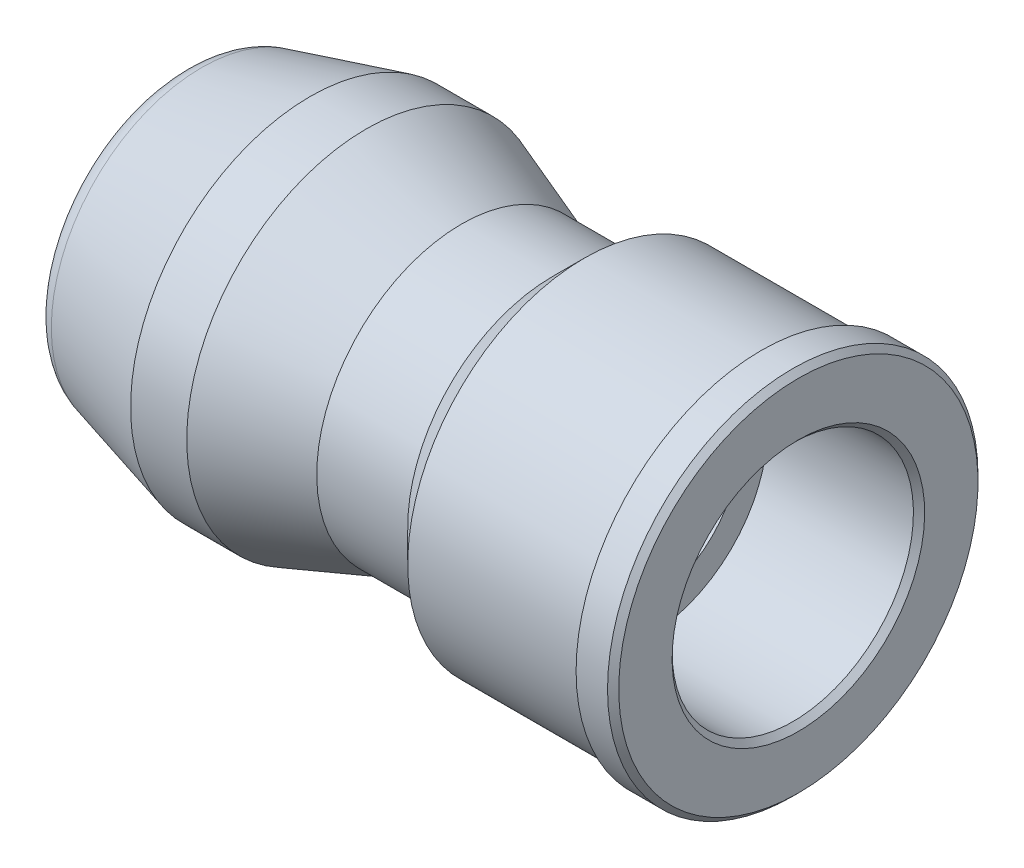
SolidWorks part; units mm, degrees
ref_plane "Front Plane" through (0, 0, 0) normal (0, 0, 1) x (1, 0, 0)
ref_plane "Top Plane" through (0, 0, 0) normal (0, 1, 0) x (1, 0, 0)
ref_plane "Right Plane" through (0, 0, 0) normal (1, 0, 0) x (0, 0, -1)
sketch "Sketch1" plane through (0, 0, 0) normal (0, 0, 1) x (1, 0, 0)
  line L0 (0, 0) -> (0, 2.58)
  line L1 (0, 2.58) -> (2.3, 3.1963)
  line L2 (2.3, 3.1963) -> (3.3, 3.1963)
  line L3 (3.3, 3.1963) -> (5, 2.58)
  line L4 (5, 2.58) -> (6.62, 2.58)
  line L6 (7.19, 3.15) -> (10.34, 3.15)
  line L7 (10.34, 3.15) -> (10.34, 3.3)
  line L8 (10.34, 3.3) -> (11, 3.3)
  line L9 (11, 3.3) -> (11, 2.15)
  line L10 (11, 2.15) -> (8.3, 2.15)
  line L11 (8.3, 2.15) -> (8.3, 0)
  line L12 (8.3, 0) -> (0, 0)
  line L13 (6.62, 2.58) -> (7.19, 3.15)
  dimension "D1" = 2.58
  dimension "D2" = 8.3
  dimension "D3" = 2.3
  dimension "D4" = 1.7
  dimension "D5" = 105
  dimension "D6" = 135
  dimension "D7" = 1
  dimension "D8" = 1.62
  dimension "D9" = 3.15
  dimension "D10" = 1.15
  dimension "D11" = 2.15
  dimension "D12" = 2.7
  dimension "D13" = 1
revolve "Revolve1" add sketch "Sketch1" angle 360 about L12
hole_wizard "M4 Tapped Hole1" positions "Sketch2" profile "Sketch3" tap size "M4" standard "ISO" end condition through all
sketch "Sketch2" plane through (0, 0, 0) normal (-1, 0, 0) x (0, 0, 1)
  point P0 (0, 0)
sketch "Sketch3" plane through (0, 0, 0) normal (0, 1, 0) x (0, 0, 1)
  line L0 (0, 0) -> (0, 11)
  line L1 (0, 11) -> (1.65, 11)
  line L2 (1.65, 11) -> (1.65, 0.9053)
  line L3 (1.65, 0.9053) -> (2.025, 0)
  line L5 (2.025, 0) -> (0, 0)
  line L6 (-1.65, 0.9053) -> (-2.025, 0) construction
  line L11 (0, -6.35) -> (0, 107.95) construction
  dimension "Thru Tap Drill Dia." = 3.3
  dimension "Thru Tap Drill Depth" = 11
  dimension "Near C'Sink Dia." = 4.05
  dimension "Near C'Sink Angle" = 45
cosmetic thread "Hole Thread1" parameters "D2"=4
fillet "Fillet1" radius 0.5 1 edges at (0, 2.58, 0)
chamfer "Chamfer1" distance 0.1 angle 45 3 edges at (11, 3.3, 0) (10.34, 3.15, 0) (11, 2.15, 0)
